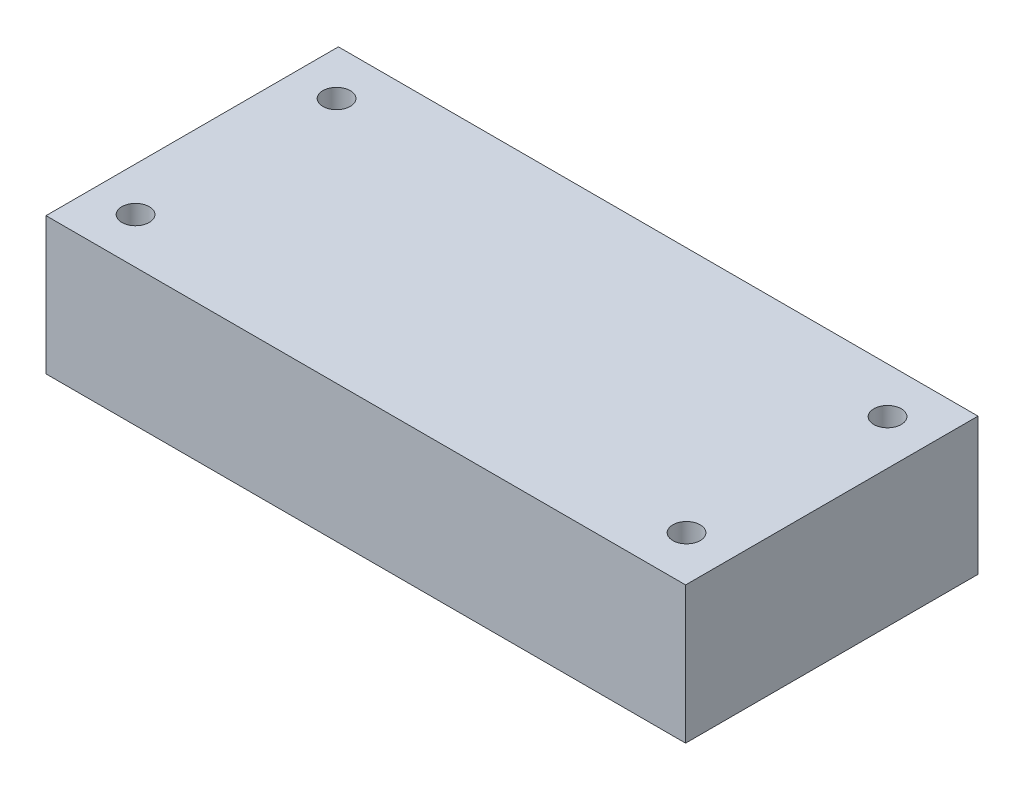
SolidWorks part; units mm, degrees
ref_plane "Front Plane" through (0, 0, 0) normal (0, 0, 1) x (1, 0, 0)
ref_plane "Top Plane" through (0, 0, 0) normal (0, 1, 0) x (1, 0, 0)
ref_plane "Right Plane" through (0, 0, 0) normal (1, 0, 0) x (0, 0, -1)
sketch "Sketch1" plane through (0, 0, 0) normal (0, 1, 0) x (1, 0, 0)
  line L1 (-35, -16) -> (35, -16)
  line L2 (-35, -16) -> (-35, 16)
  line L3 (-35, 16) -> (35, 16)
  line L4 (35, -16) -> (35, 16)
  line L5 (-35, -16) -> (35, 16) construction
  line L6 (-35, 16) -> (35, -16) construction
  circle A0 centre (-30.2, 11) radius 1.5
  circle A1 centre (30.1, 11) radius 1.5
  circle A2 centre (30.1, -11) radius 1.5
  circle A3 centre (-30.2, -11) radius 1.5
  point P0 (0, 0)
  dimension "D3" = 3
  dimension "D4" = 3
  dimension "D5" = 3
  dimension "D6" = 3
  dimension "D1" = 70
  dimension "D2" = 32
  dimension "D7" = 5
  dimension "D8" = 4.8
  dimension "D9" = 4.9
  dimension "D10" = 5
  dimension "D11" = 5
  dimension "D12" = 5
  dimension "D13" = 4.8
  dimension "D14" = 4.9
extrude "Boss-Extrude1" add sketch "Sketch1" along normal blind 15
